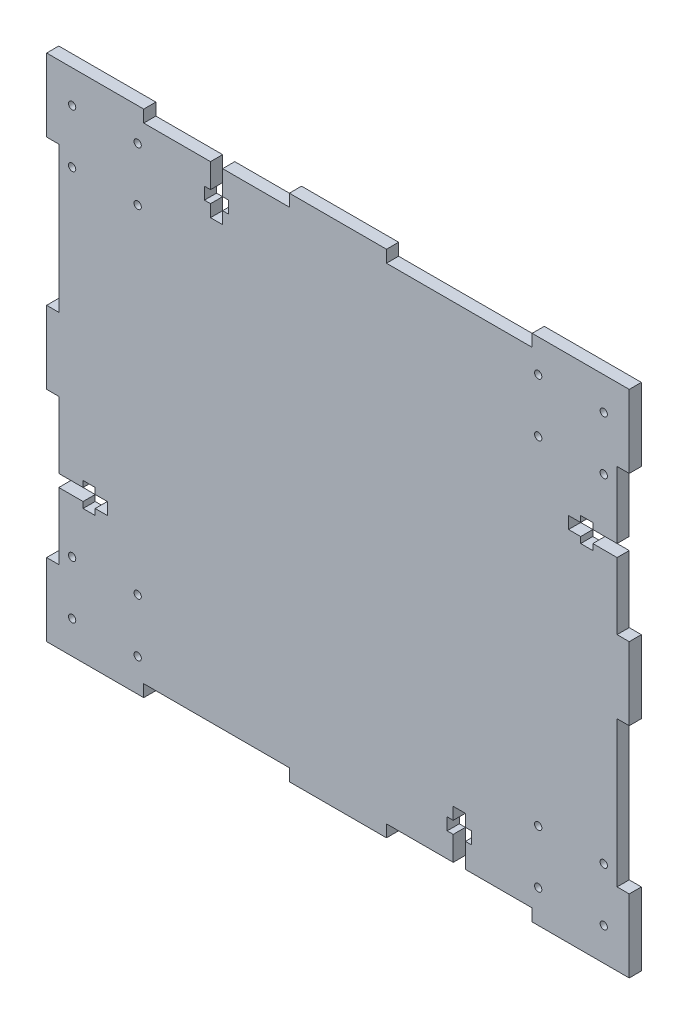
SolidWorks part; units mm, degrees
ref_plane "Plan de face" through (0, 0, 0) normal (0, 0, 1) x (1, 0, 0)
ref_plane "Plan de dessus" through (0, 0, 0) normal (0, 1, 0) x (1, 0, 0)
ref_plane "Plan de droite" through (0, 0, 0) normal (1, 0, 0) x (0, 0, -1)
sketch "Esquisse1" plane through (0, 0, 0) normal (0, 0, 1) x (1, 0, 0)
  line L0 (-25, 81.2903) -> (15, 81.2903)
  line L1 (15, 81.2903) -> (15, 76.2903)
  line L2 (15, 76.2903) -> (75, 76.2903)
  line L3 (75, 76.2903) -> (75, 81.2903)
  line L4 (75, 81.2903) -> (115, 81.2903)
  line L5 (115, 81.2903) -> (115, 51.2903)
  line L6 (115, 51.2903) -> (110, 51.2903)
  line L7 (110, 51.2903) -> (110, 23.7903)
  line L8 (110, -8.7097) -> (115, -8.7097)
  line L9 (115, -8.7097) -> (115, -38.7097)
  line L10 (-5, 81.2903) -> (-5, -23.7097) construction
  line L11 (-5, -23.7097) -> (115, -23.7097) construction
  line L12 (75, -128.7097) -> (115, -128.7097)
  line L13 (-25, -128.7097) -> (15, -128.7097)
  line L14 (75, -123.7097) -> (75, -128.7097)
  line L15 (15, -123.7097) -> (42.5, -123.7097)
  line L16 (15, -128.7097) -> (15, -123.7097)
  line L17 (110, -38.7097) -> (115, -38.7097)
  line L18 (110, -98.7097) -> (110, -38.7097)
  line L19 (115, -98.7097) -> (110, -98.7097)
  line L20 (115, -128.7097) -> (115, -98.7097)
  line L21 (-85, 76.2903) -> (-85, 81.2903)
  line L22 (-25, 81.2903) -> (-25, 76.2903)
  line L23 (-25, -128.7097) -> (-25, -123.7097)
  line L24 (-25, -123.7097) -> (-85, -123.7097)
  line L25 (-85, -123.7097) -> (-85, -128.7097)
  line L26 (-85, -128.7097) -> (-125, -128.7097)
  line L27 (-125, -128.7097) -> (-125, -98.7097)
  line L28 (-125, -98.7097) -> (-120, -98.7097)
  line L29 (-120, -98.7097) -> (-120, -71.2097)
  line L30 (-120, -38.7097) -> (-125, -38.7097)
  line L31 (-125, -8.7097) -> (-125, -38.7097)
  line L32 (-120, -8.7097) -> (-125, -8.7097)
  line L33 (-120, 51.2903) -> (-120, -8.7097)
  line L34 (-125, 51.2903) -> (-120, 51.2903)
  line L35 (-125, 81.2903) -> (-125, 51.2903)
  line L36 (-85, 81.2903) -> (-125, 81.2903)
  line L37 (-25, 76.2903) -> (-52.5, 76.2903)
  line L38 (110, 21.2903) -> (77.5146, 21.2903) construction
  line L39 (-55, 76.2903) -> (-55, 52.3023) construction
  line L40 (-120, -68.7097) -> (-90.4149, -68.7097) construction
  line L41 (45, -123.7097) -> (45, -104.8387) construction
  line L42 (110, 23.7903) -> (100, 23.7903)
  line L43 (100, 23.7903) -> (100, 26.2903)
  line L44 (100, 26.2903) -> (95, 26.2903)
  line L45 (95, 26.2903) -> (95, 23.7903)
  line L46 (95, 23.7903) -> (90, 23.7903)
  line L47 (-52.5, 76.2903) -> (-52.5, 66.2903)
  line L48 (-52.5, 66.2903) -> (-50, 66.2903)
  line L49 (-50, 66.2903) -> (-50, 61.2903)
  line L50 (-50, 61.2903) -> (-52.5, 61.2903)
  line L51 (-52.5, 61.2903) -> (-52.5, 56.2903)
  line L52 (-120, -66.2097) -> (-110, -66.2097)
  line L53 (-110, -66.2097) -> (-110, -63.7097)
  line L54 (-110, -63.7097) -> (-105, -63.7097)
  line L55 (-105, -63.7097) -> (-105, -66.2097)
  line L56 (-105, -66.2097) -> (-100, -66.2097)
  line L57 (47.5, -123.7097) -> (47.5, -113.7097)
  line L58 (47.5, -113.7097) -> (50, -113.7097)
  line L59 (50, -113.7097) -> (50, -108.7097)
  line L60 (50, -108.7097) -> (47.5, -108.7097)
  line L61 (47.5, -108.7097) -> (47.5, -103.7097)
  line L62 (95, 18.7903) -> (90, 18.7903)
  line L63 (110, 18.7903) -> (100, 18.7903)
  line L64 (95, 16.2903) -> (95, 18.7903)
  line L65 (100, 16.2903) -> (95, 16.2903)
  line L66 (100, 18.7903) -> (100, 16.2903)
  line L67 (-57.5, 76.2903) -> (-57.5, 66.2903)
  line L68 (-57.5, 61.2903) -> (-57.5, 56.2903)
  line L69 (-60, 61.2903) -> (-57.5, 61.2903)
  line L70 (-60, 66.2903) -> (-60, 61.2903)
  line L71 (-57.5, 66.2903) -> (-60, 66.2903)
  line L72 (-120, -71.2097) -> (-110, -71.2097)
  line L73 (-105, -71.2097) -> (-100, -71.2097)
  line L74 (-105, -73.7097) -> (-105, -71.2097)
  line L75 (-110, -73.7097) -> (-105, -73.7097)
  line L76 (-110, -71.2097) -> (-110, -73.7097)
  line L77 (-100, -66.2097) -> (-100, -71.2097)
  line L78 (-57.5, 56.2903) -> (-52.5, 56.2903)
  line L79 (90, 23.7903) -> (90, 18.7903)
  line L80 (42.5, -123.7097) -> (42.5, -113.7097)
  line L81 (42.5, -108.7097) -> (42.5, -103.7097)
  line L82 (40, -108.7097) -> (42.5, -108.7097)
  line L83 (40, -113.7097) -> (40, -108.7097)
  line L84 (42.5, -113.7097) -> (40, -113.7097)
  line L85 (42.5, -103.7097) -> (47.5, -103.7097)
  line L86 (-57.5, 76.2903) -> (-85, 76.2903)
  line L87 (110, 18.7903) -> (110, -8.7097)
  line L88 (-120, -66.2097) -> (-120, -38.7097)
  line L89 (47.5, -123.7097) -> (75, -123.7097)
  circle A0 centre (-114.5, -93.2097) radius 1.5
  circle A1 centre (-114.5, -115.2097) radius 1.5
  circle A2 centre (-87.5, -115.2097) radius 1.5
  circle A3 centre (-87.5, -93.2097) radius 1.5
  circle A4 centre (-87.5, 45.7903) radius 1.5
  circle A5 centre (-87.5, 67.7903) radius 1.5
  circle A6 centre (-114.5, 67.7903) radius 1.5
  circle A7 centre (-114.5, 45.7903) radius 1.5
  circle A8 centre (104.5, 67.7903) radius 1.5
  circle A9 centre (104.5, 45.7903) radius 1.5
  circle A10 centre (77.5, 45.7903) radius 1.5
  circle A11 centre (77.5, 67.7903) radius 1.5
  circle A12 centre (104.5, -93.2097) radius 1.5
  circle A13 centre (104.5, -115.2097) radius 1.5
  circle A14 centre (77.5, -115.2097) radius 1.5
  circle A15 centre (77.5, -93.2097) radius 1.5
  point P27 (-5, -128.7097)
  dimension "D12" = 3
  dimension "D13" = 22
  dimension "D14" = 10.5
  dimension "D15" = 13.5
  dimension "D16" = 27
  dimension "D19" = 22
  dimension "D1" = 20
  dimension "D2" = 60
  dimension "D3" = 40
  dimension "D4" = 30
  dimension "D5" = 60
  dimension "D6" = 15
  dimension "D7" = 5
  dimension "D8" = 5
  dimension "D9" = 10
  dimension "D10" = 2.5
  dimension "D11" = 5
  dimension "D17" = 5
  dimension "D18" = 10.5
extrude "Boss.-Extru.1" add sketch "Esquisse1" along normal blind 5
